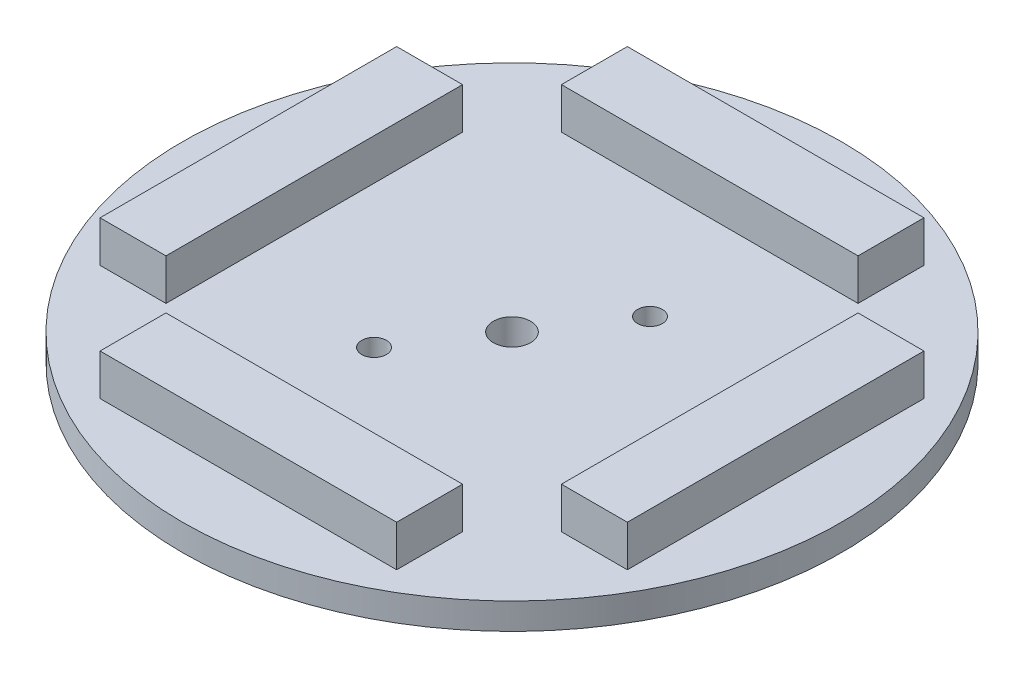
SolidWorks part; units mm, degrees
material "A-Glass Fiber"
ref_plane "Front Plane" through (0, 0, 0) normal (0, 0, 1) x (1, 0, 0)
ref_plane "Top Plane" through (0, 0, 0) normal (0, 1, 0) x (1, 0, 0)
ref_plane "Right Plane" through (0, 0, 0) normal (1, 0, 0) x (0, 0, -1)
sketch "Sketch1" plane through (0, 0, 0) normal (0, 1, 0) x (1, 0, 0)
  line L0 (-11.1839, -16.5808) -> (11.1839, 16.5808) construction
  line L1 (0, 20) -> (0, -20) construction
  circle A0 centre (0, 0) radius 20
  circle A1 centre (0, 0) radius 1.1303
  circle A2 centre (3.3725, 5) radius 0.75
  circle A3 centre (-3.3725, -5) radius 0.75
  dimension "D1" = 40
  dimension "D5" = 2.2606
  dimension "D6" = 1.5
  dimension "D7" = 1.5
  dimension "D2" = 34
  dimension "D3" = 5
  dimension "D4" = 5
extrude "PCB" add sketch "Sketch1" along normal blind 1.6 contours A0 | A3 | A1 | A2
sketch "Sketch2" plane through (0, 1.6, 0) normal (0, 1, 0) x (1, 0, 0)
  line L0 (0, 20) -> (0, 0) construction
  line L1 (-9, 16) -> (9, 16)
  line L2 (-9, 16) -> (-9, 12)
  line L3 (-9, 12) -> (9, 12)
  line L4 (9, 16) -> (9, 12)
  circle A0 centre (0, 0) radius 20 construction
  point P9 (0, 16)
  dimension "D1" = 4
  dimension "D2" = 18
  dimension "D3" = 16
extrude "Hirose Connector Stack" add sketch "Sketch2" along normal blind 2.5 contours L1 L4 L3 L2
pattern_circular "CirPattern1" count 4 over 360 about axis through (0, 0, 0) along (0, 1, 0) of "Hirose Connector Stack"
